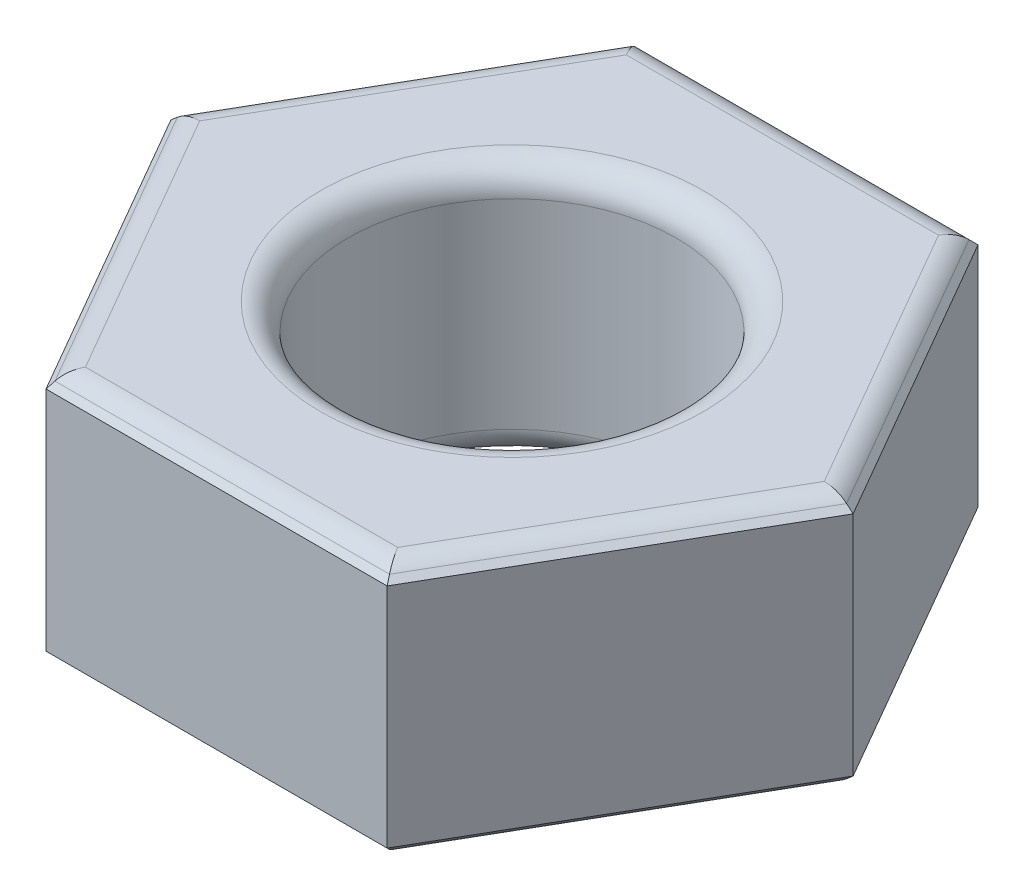
SolidWorks part; units mm, degrees
ref_plane "Front Plane" through (0, 0, 0) normal (0, 0, 1) x (1, 0, 0)
ref_plane "Top Plane" through (0, 0, 0) normal (0, 1, 0) x (1, 0, 0)
ref_plane "Right Plane" through (0, 0, 0) normal (1, 0, 0) x (0, 0, -1)
sketch "Sketch1" plane through (0, 0, 0) normal (0, 1, 0) x (1, 0, 0)
  line L1 (3.1177, 0) -> (1.5588, 2.7)
  line L2 (1.5588, 2.7) -> (-1.5588, 2.7)
  line L3 (-1.5588, 2.7) -> (-3.1177, 0)
  line L4 (-3.1177, 0) -> (-1.5588, -2.7)
  line L5 (-1.5588, -2.7) -> (1.5588, -2.7)
  line L6 (1.5588, -2.7) -> (3.1177, 0)
  circle A0 centre (0, 0) radius 2.7 construction
  circle A1 centre (0, 0) radius 1.5
  dimension "D2" = 3
  dimension "D1" = 5.4
extrude "Boss-Extrude1" add sketch "Sketch1" along normal blind 2.325
chamfer "Chamfer1" distance 0.125 angle 45 12 edges at (2.3383, 0, -1.35) (0, 0, -2.7) (-2.3383, 0, -1.35) (2.3383, 0, 1.35) (0, 0, 2.7) (-2.3383, 0, 1.35) (0, 2.325, 2.7) (2.3383, 2.325, 1.35) (2.3383, 2.325, -1.35) (0, 2.325, -2.7) (-2.3383, 2.325, -1.35) (-2.3383, 2.325, 1.35)
fillet "Fillet1" radius 0.25 14 edges at (0, 2.325, 1.5) (-2.23, 2.325, -1.2875) (0, 2.325, -2.575) (2.23, 2.325, -1.2875) (2.23, 2.325, 1.2875) (0, 2.325, 2.575) (-2.23, 2.325, 1.2875) (0, 0, 1.5) (-2.23, 0, -1.2875) (-2.23, 0, 1.2875) (0, 0, 2.575) (2.23, 0, 1.2875) (2.23, 0, -1.2875) (0, 0, -2.575)
